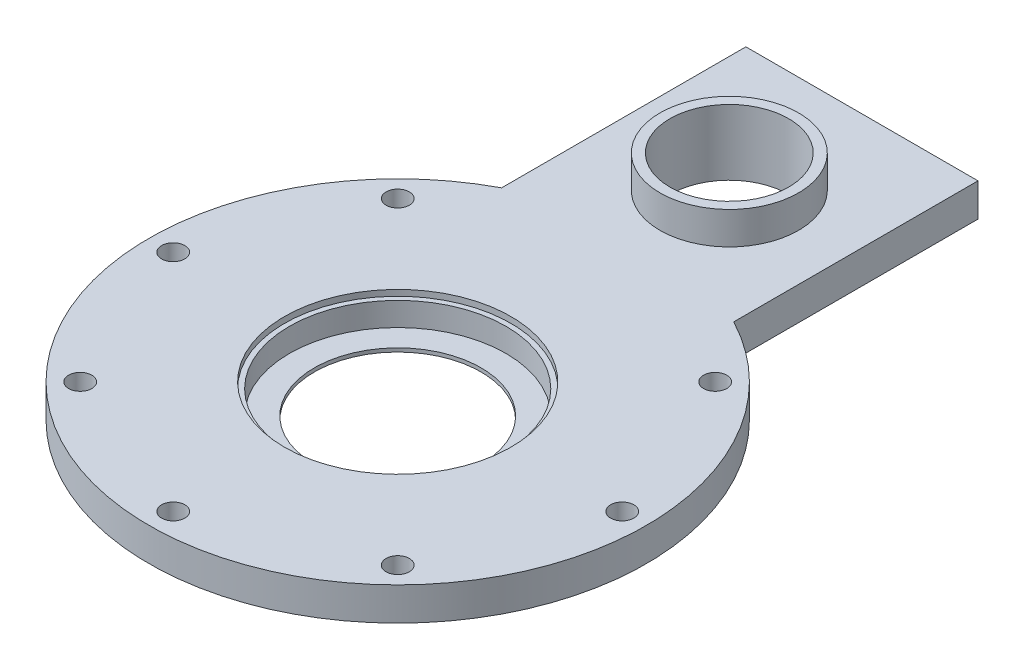
SolidWorks part; units mm, degrees
ref_plane "前视基准面" through (0, 0, 0) normal (0, 0, 1) x (1, 0, 0)
ref_plane "上视基准面" through (0, 0, 0) normal (0, 1, 0) x (1, 0, 0)
ref_plane "右视基准面" through (0, 0, 0) normal (1, 0, 0) x (0, 0, -1)
other "Configuration Table"
sketch "草图1" plane through (0, 0, 0) normal (0, 1, 0) x (1, 0, 0)
  line L0 (63.6867, -87) -> (44.0908, 9)
  line L1 (-44.0908, 9) -> (-63.6867, -87)
  arc A0 (44.0908, 9) -> (-44.0908, 9) centre (0, 0) ccw
  arc A1 (-63.6867, -87) -> (63.6867, -87) centre (0, -100) ccw
extrude "凸台-拉伸1" add sketch "草图1" along normal blind 10
sketch "草图2" plane through (0, 10, 0) normal (0, 1, 0) x (1, 0, 0)
  circle A0 centre (0, 0) radius 17.9
  circle A1 centre (0, -100) radius 25.15
  dimension "D1" = 35.8
  dimension "D2" = 50.3
extrude "切除-拉伸1" cut sketch "草图2" against normal through all
sketch "草图4" plane through (0, 10, 0) normal (0, 1, 0) x (1, 0, 0)
  circle A0 centre (0, -100) radius 34.15
  dimension "D1" = 68.3
extrude "切除-拉伸2" cut sketch "草图4" against normal blind 1.8
sketch "草图5" plane through (0, 8.2, 0) normal (0, 1, 0) x (1, 0, 0)
  circle A0 centre (0, -100) radius 32.65
  dimension "D1" = 65.3
extrude "切除-拉伸3" cut sketch "草图5" against normal blind 7.1
sketch "草图6" plane through (0, 10, 0) normal (0, 1, 0) x (1, 0, 0)
  circle A0 centre (0, 0) radius 17.9 construction
  circle A1 centre (0, 0) radius 17.9
  circle A4 centre (0, 0) radius 20.9
  dimension "D1" = 3
extrude "凸台-拉伸2" add sketch "草图6" along normal blind 9.8
sketch "草图7" plane through (0, 0, 0) normal (0, -1, 0) x (1, 0, 0)
  line L17 (0, 100) -> (0, 0)
  line L21 (45, -40) -> (-45, -40)
  line L22 (-63.6867, 87) -> (-44.0908, -9)
  line L23 (44.0908, -9) -> (63.6867, 87)
  line L24 (-63.6867, 87) -> (-44.0908, -9)
  line L25 (44.0908, -9) -> (63.6867, 87)
  line L26 (45, -40) -> (45, 60)
  line L27 (-63.6867, 87) -> (-44.0908, -9)
  line L28 (44.0908, -9) -> (63.6867, 87)
  line L29 (45, 60) -> (-45, 60)
  line L30 (-45, -40) -> (-45, 60)
  line L31 (45, -40) -> (-45, 60) construction
  line L32 (45, 60) -> (-45, -40) construction
  circle A11 centre (0, 100) radius 75
  arc A16 (63.6867, 87) -> (-63.6867, 87) centre (0, 100) ccw
  arc A17 (63.6867, 87) -> (-63.6867, 87) centre (0, 100) ccw
  arc A18 (-44.0908, -9) -> (44.0908, -9) centre (0, 0) ccw
  arc A19 (63.6867, 87) -> (-63.6867, 87) centre (0, 100) ccw
  arc A20 (-44.0908, -9) -> (44.0908, -9) centre (0, 0) ccw
  point P0 (0, 10)
  dimension "D2" = 150
  dimension "D3" = 90
  dimension "D4" = 0
  dimension "D5" = 10
  dimension "D6" = 100
  dimension "D1" = 0
extrude "凸台-拉伸3" add sketch "草图7" against normal up to surface (10 mm away)
sketch "草图8" plane through (0, 0, 0) normal (0, -1, 0) x (1, 0, 0)
  line L13 (0, 100) -> (0, 0)
  line L14 (45, -40) -> (-45, -40)
  line L15 (45, -40) -> (45, 60)
  line L16 (-63.6867, 87) -> (-44.0908, -9)
  line L17 (44.0908, -9) -> (63.6867, 87)
  line L18 (45, 60) -> (-45, 60)
  line L19 (-45, -40) -> (-45, 60)
  line L20 (45, -40) -> (-45, 60) construction
  line L21 (45, 60) -> (-45, -40) construction
  line L23 (-45, -40) -> (45, -40)
  line L24 (-45, -40) -> (-45, -79.9277)
  line L25 (-45, -79.9277) -> (45, -79.9277)
  line L26 (45, -40) -> (45, -79.9277)
  circle A3 centre (0, 100) radius 75
  arc A4 (63.6867, 87) -> (-63.6867, 87) centre (0, 100) ccw
  point P0 (0, 10)
  dimension "D1" = 150
  dimension "D2" = 90
  dimension "D3" = 0
  dimension "D4" = 10
  dimension "D5" = 100
extrude "切除-拉伸4" cut sketch "草图8" against normal through all
sketch "草图10" plane through (0, 0, 0) normal (0, -1, 0) x (1, 0, 0)
  line L6 (45, -40) -> (45, 40)
  line L9 (45, -40) -> (45, 40)
  line L20 (-45, -40) -> (45, -40)
  line L21 (-45, -40) -> (45, -40)
  line L34 (-45, 40) -> (-45, -40)
  line L35 (-45, 40) -> (-45, -40)
  arc A11 (45, 40) -> (-45, 40) centre (0, 100) ccw
  arc A12 (45, 40) -> (-45, 40) centre (0, 100) ccw
  dimension "D1" = 0
sketch "草图11" plane through (0, 10, 0) normal (0, 1, 0) x (1, 0, 0)
  line L0 (-45, 40) -> (-45, -40)
  line L1 (45, -40) -> (45, 40)
  line L2 (45, 40) -> (-45, 40)
  arc A0 (-45, -40) -> (45, -40) centre (0, -100) ccw
  circle A1 centre (0, -167.7) radius 3.5
  circle A2 centre (47.8711, -147.8711) radius 3.5
  circle A3 centre (-47.8711, -147.8711) radius 3.5
  circle A4 centre (-67.7, -100) radius 3.5
  circle A5 centre (-47.8711, -52.1289) radius 3.5
  circle A6 centre (67.7, -100) radius 3.5
  circle A7 centre (47.8711, -52.1289) radius 3.5
extrude "切除-拉伸5" cut sketch "草图11" against normal through all contours A7 | A6 | A2 | A1 | A3 | A4 | A5
sketch "草图12" plane through (0, 10, 0) normal (0, 1, 0) x (1, 0, 0)
  line L1 (-35, -40) -> (35, -40)
  line L2 (-35, -40) -> (-35, 40)
  line L3 (45, -40) -> (45, 40)
  line L4 (45, 40) -> (-45, 40)
  line L5 (-45, 40) -> (-45, -40)
  line L6 (45, -40) -> (45, 40)
  line L7 (45, 40) -> (-45, 40)
  line L8 (-45, 40) -> (-45, -40)
  line L9 (-35, 40) -> (35, 40)
  line L10 (35, -40) -> (35, 40)
  line L11 (-35, -40) -> (35, 40) construction
  line L12 (-35, 40) -> (35, -40) construction
  circle A0 centre (0, -100) radius 75
  arc A1 (-45, -40) -> (45, -40) centre (0, -100) ccw
  arc A2 (-45, -40) -> (45, -40) centre (0, -100) ccw
  point P6 (0, 0)
  line M13 (45, -40) -> (45, 40)
  line M14 (45, 40) -> (-45, 40)
  line M15 (-45, 40) -> (-45, -40)
  dimension "D2" = 10
  dimension "D1" = 0
extrude "切除-拉伸6" cut sketch "草图12" against normal through all contours A0 L2 M14 M15 | A0 L10 M13 M14
sketch "草图13" plane through (0, 10, 0) normal (0, 1, 0) x (1, 0, 0)
  line L3 (-35, 40) -> (-35, -33.6675)
  line L4 (35, -33.6675) -> (35, 40)
  line L5 (35, 40) -> (-35, 40)
  line L6 (-35, 40) -> (-35, -33.6675)
  line L7 (35, -33.6675) -> (35, 40)
  line L8 (35, 40) -> (-35, 40)
  arc A1 (-35, -33.6675) -> (35, -33.6675) centre (0, -100) ccw
  arc A2 (-35, -33.6675) -> (35, -33.6675) centre (0, -100) ccw
  dimension "D1" = 0
